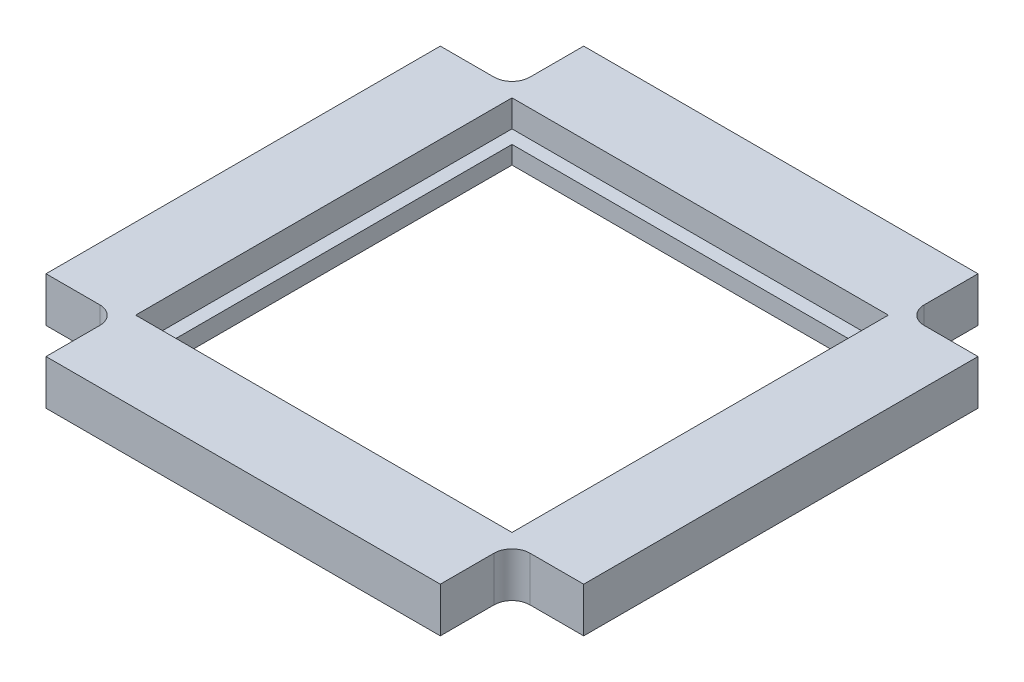
SolidWorks part; units mm, degrees
material "PP 共聚物"
ref_plane "前视基准面" through (0, 0, 0) normal (0, 0, 1) x (1, 0, 0)
ref_plane "上视基准面" through (0, 0, 0) normal (0, 1, 0) x (1, 0, 0)
ref_plane "右视基准面" through (0, 0, 0) normal (1, 0, 0) x (0, 0, -1)
sketch "草图1" plane through (0, 0, 0) normal (0, 1, 0) x (1, 0, 0)
  line L1 (-3, 3) -> (3, 3)
  line L2 (-3, 3) -> (-3, -3)
  line L3 (-3, -3) -> (3, -3)
  line L4 (3, 3) -> (3, -3)
  line L5 (-3, 3) -> (3, -3) construction
  line L6 (-3, -3) -> (3, 3) construction
  point P0 (0, 0)
  dimension "D1" = 6
  dimension "D2" = 6
extrude "凸台-拉伸1" add sketch "草图1" along normal blind 0.5
sketch "草图2" plane through (0, 0.5, 0) normal (0, 1, 0) x (1, 0, 0)
  line L1 (-1.95, 1.95) -> (1.95, 1.95)
  line L2 (-1.95, 1.95) -> (-1.95, -1.95)
  line L3 (-1.95, -1.95) -> (1.95, -1.95)
  line L4 (1.95, 1.95) -> (1.95, -1.95)
  line L5 (-1.95, 1.95) -> (1.95, -1.95) construction
  line L6 (-1.95, -1.95) -> (1.95, 1.95) construction
  point P0 (0, 0)
  dimension "D1" = 3.9
  dimension "D2" = 3.9
extrude "切除-拉伸1" cut sketch "草图2" against normal through all
sketch "草图3" plane through (0, 0.5, 0) normal (0, 1, 0) x (1, 0, 0)
  line L1 (2.1, 2.1) -> (-2.1, 2.1)
  line L2 (2.1, 2.1) -> (2.1, -2.1)
  line L3 (2.1, -2.1) -> (-2.1, -2.1)
  line L4 (-2.1, 2.1) -> (-2.1, -2.1)
  line L5 (2.1, 2.1) -> (-2.1, -2.1) construction
  line L6 (2.1, -2.1) -> (-2.1, 2.1) construction
  point P0 (0, 0)
  dimension "D1" = 4.2
  dimension "D2" = 4.2
extrude "切除-拉伸2" cut sketch "草图3" against normal blind 0.3
sketch "草图4" plane through (0, 0.5, 0) normal (0, 1, 0) x (1, 0, 0)
  line L1 (-3, 3) -> (-2.2, 3)
  line L2 (-3, 3) -> (-3, 2.2)
  line L3 (-3, 2.2) -> (-2.2, 2.2)
  line L4 (-2.2, 3) -> (-2.2, 2.2)
  line L5 (3, 3) -> (2.2, 3)
  line L6 (3, 3) -> (3, 2.2)
  line L7 (3, 2.2) -> (2.2, 2.2)
  line L8 (2.2, 3) -> (2.2, 2.2)
  line L9 (-3, -3) -> (-2.2, -3)
  line L10 (-3, -3) -> (-3, -2.2)
  line L11 (-3, -2.2) -> (-2.2, -2.2)
  line L12 (-2.2, -3) -> (-2.2, -2.2)
  line L13 (3, -3) -> (2.2, -3)
  line L14 (3, -3) -> (3, -2.2)
  line L15 (3, -2.2) -> (2.2, -2.2)
  line L16 (2.2, -3) -> (2.2, -2.2)
  dimension "D1" = 0.8
  dimension "D2" = 0.8
  dimension "D3" = 0.8
  dimension "D4" = 0.8
  dimension "D5" = 0.8
  dimension "D6" = 0.8
  dimension "D7" = 0.8
  dimension "D8" = 0.8
extrude "切除-拉伸3" cut sketch "草图4" against normal through all
fillet "圆角2" radius 0.2 4 edges at (2.2, 0.25, 2.2) (2.2, 0.25, -2.2) (-2.2, 0.25, -2.2) (-2.2, 0.25, 2.2)
